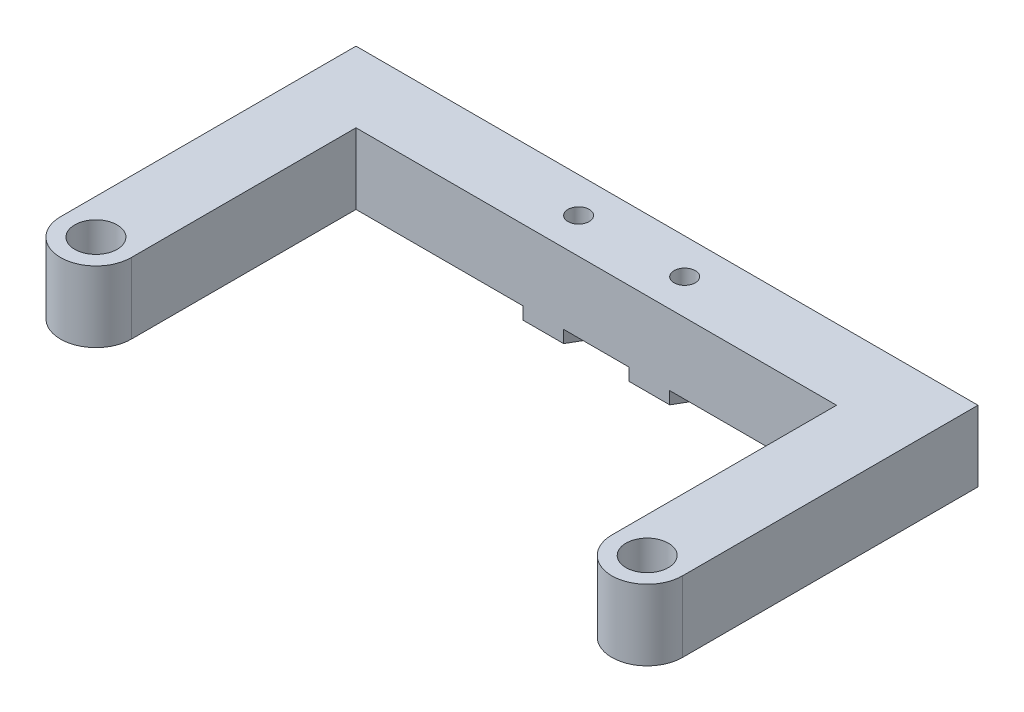
SolidWorks part; units mm, degrees
ref_plane "Front Plane" through (0, 0, 0) normal (0, 0, 1) x (1, 0, 0)
ref_plane "Top Plane" through (0, 0, 0) normal (0, 1, 0) x (1, 0, 0)
ref_plane "Right Plane" through (0, 0, 0) normal (1, 0, 0) x (0, 0, -1)
sketch "Sketch1" plane through (0, 0, 0) normal (0, 1, 0) x (1, 0, 0)
  line L0 (0, 0) -> (0, 45) construction
  line L1 (-38.9711, 22.5) -> (0, 0) construction
  line L3 (-43.9711, 22.5) -> (-33.9711, 22.5)
  line L4 (-43.9711, 22.5) -> (-43.9711, 64.2721)
  line L5 (-43.9711, 64.2721) -> (-33.9711, 64.2721)
  line L6 (-33.9711, 22.5) -> (-33.9711, 64.2721)
  line L7 (-43.9711, 22.5) -> (-33.9711, 64.2721) construction
  line L8 (-43.9711, 64.2721) -> (-33.9711, 22.5) construction
  line L9 (-33.9711, 64.2721) -> (33.9711, 64.2721)
  line L10 (-33.9711, 64.2721) -> (-33.9711, 54.2721)
  line L11 (-33.9711, 54.2721) -> (33.9711, 54.2721)
  line L12 (33.9711, 64.2721) -> (33.9711, 54.2721)
  line L13 (-33.9711, 64.2721) -> (33.9711, 54.2721) construction
  line L14 (-33.9711, 54.2721) -> (33.9711, 64.2721) construction
  line L15 (43.9711, 22.5) -> (33.9711, 22.5)
  line L16 (43.9711, 22.5) -> (43.9711, 64.2721)
  line L17 (43.9711, 64.2721) -> (33.9711, 64.2721)
  line L18 (33.9711, 22.5) -> (33.9711, 64.2721)
  line L19 (43.9711, 22.5) -> (33.9711, 64.2721) construction
  line L20 (43.9711, 64.2721) -> (33.9711, 22.5) construction
  circle A0 centre (0, 0) radius 45 construction
  circle A1 centre (-38.9711, 22.5) radius 1.5
  circle A2 centre (38.9711, 22.5) radius 1.5
  circle A3 centre (-38.9711, 22.5) radius 5
  circle A4 centre (38.9711, 22.5) radius 5
  circle A7 centre (-7.5, 59.2721) radius 1.5
  circle A8 centre (7.5, 59.2721) radius 1.5
  arc A9 (-38.9711, 22.5) -> (38.9711, 22.5) centre (0, 21) cw construction
  point P18 (-38.9711, 43.386)
  point P23 (0, 59.2721)
  point P28 (38.9711, 43.386)
  dimension "D1" = 90
  dimension "D2" = 3
  dimension "D4" = 10
  dimension "D5" = 3
  dimension "D7" = 39
  dimension "D3" = 60
  dimension "D6" = 15
extrude "Boss-Extrude1" add sketch "Sketch1" along normal blind 10
sketch "Sketch2" plane through (0, 0, 0) normal (0, -1, 0) x (1, 0, 0)
  line L0 (-4.6132, -54.2721) -> (-10.3868, -54.2721)
  line L1 (-5.7679, -56.2721) -> (-9.2321, -56.2721)
  line L2 (-9.2321, -56.2721) -> (-10.9641, -59.2721)
  line L3 (-10.9641, -59.2721) -> (-9.2321, -62.2721)
  line L4 (-9.2321, -62.2721) -> (-5.7679, -62.2721)
  line L5 (-5.7679, -62.2721) -> (-4.0359, -59.2721)
  line L6 (-4.0359, -59.2721) -> (-5.7679, -56.2721)
  line L7 (9.2321, -56.2721) -> (5.7679, -56.2721)
  line L8 (5.7679, -56.2721) -> (4.0359, -59.2721)
  line L9 (4.0359, -59.2721) -> (5.7679, -62.2721)
  line L10 (5.7679, -62.2721) -> (9.2321, -62.2721)
  line L11 (9.2321, -62.2721) -> (10.9641, -59.2721)
  line L12 (10.9641, -59.2721) -> (9.2321, -56.2721)
  line L13 (-10.3868, -54.2721) -> (-13.2735, -59.2721)
  line L14 (-13.2735, -59.2721) -> (-10.3868, -64.2721)
  line L15 (-10.3868, -64.2721) -> (-4.6132, -64.2721)
  line L16 (-4.6132, -64.2721) -> (-1.7265, -59.2721)
  line L17 (-1.7265, -59.2721) -> (-4.6132, -54.2721)
  line L19 (10.3868, -54.2721) -> (4.6132, -54.2721)
  line L20 (4.6132, -54.2721) -> (1.7265, -59.2721)
  line L21 (1.7265, -59.2721) -> (4.6132, -64.2721)
  line L22 (4.6132, -64.2721) -> (10.3868, -64.2721)
  line L23 (10.3868, -64.2721) -> (13.2735, -59.2721)
  line L24 (13.2735, -59.2721) -> (10.3868, -54.2721)
  line L26 (-43.9711, -22.5) -> (-43.9711, -64.2721)
  line L28 (-43.9711, -22.5) -> (-43.9711, -64.2721)
  line L34 (-43.9711, -64.2721) -> (43.9711, -64.2721)
  line L35 (-43.9711, -64.2721) -> (43.9711, -64.2721)
  line L36 (43.9711, -64.2721) -> (43.9711, -22.5)
  line L37 (43.9711, -64.2721) -> (43.9711, -22.5)
  line L38 (33.9711, -22.5) -> (33.9711, -54.2721)
  line L39 (33.9711, -22.5) -> (33.9711, -54.2721)
  line L40 (33.9711, -54.2721) -> (-33.9711, -54.2721)
  line L41 (33.9711, -54.2721) -> (-33.9711, -54.2721)
  line L42 (-33.9711, -54.2721) -> (-33.9711, -22.5)
  line L43 (-33.9711, -54.2721) -> (-33.9711, -22.5)
  circle A0 centre (-7.5, -59.2721) radius 1.5 construction
  circle A1 centre (7.5, -59.2721) radius 1.5 construction
  circle A2 centre (-7.5, -59.2721) radius 1.5
  circle A3 centre (7.5, -59.2721) radius 1.5
  circle A4 centre (-7.5, -59.2721) radius 3 construction
  circle A5 centre (7.5, -59.2721) radius 3 construction
  circle A6 centre (7.5, -59.2721) radius 5 construction
  arc A9 (43.9711, -22.5) -> (33.9711, -22.5) centre (38.9711, -22.5) ccw
  arc A10 (-33.9711, -22.5) -> (-43.9711, -22.5) centre (-38.9711, -22.5) ccw
  arc A12 (43.9711, -22.5) -> (33.9711, -22.5) centre (38.9711, -22.5) ccw
  arc A14 (-33.9711, -22.5) -> (-43.9711, -22.5) centre (-38.9711, -22.5) ccw
  dimension "D1" = 6
  dimension "D2" = 2
  dimension "D3" = 0
extrude "Boss-Extrude2" add sketch "Sketch2" along normal blind 1.75
sketch "Sketch3" plane through (0, 10, 0) normal (0, 1, 0) x (1, 0, 0)
  line L18 (-33.9711, 22.5) -> (-33.9711, 54.2721)
  line L19 (-33.9711, 54.2721) -> (33.9711, 54.2721)
  line L20 (33.9711, 54.2721) -> (33.9711, 22.5)
  line L21 (43.9711, 22.5) -> (43.9711, 64.2721)
  line L22 (43.9711, 64.2721) -> (-43.9711, 64.2721)
  line L23 (-43.9711, 64.2721) -> (-43.9711, 22.5)
  line L24 (-33.9711, 22.5) -> (-33.9711, 54.2721)
  line L25 (-33.9711, 54.2721) -> (33.9711, 54.2721)
  line L26 (33.9711, 54.2721) -> (33.9711, 22.5)
  line L27 (43.9711, 22.5) -> (43.9711, 64.2721)
  line L28 (43.9711, 64.2721) -> (-43.9711, 64.2721)
  line L29 (-43.9711, 64.2721) -> (-43.9711, 22.5)
  circle A0 centre (-38.9711, 22.5) radius 3
  circle A1 centre (38.9711, 22.5) radius 3
  arc A3 (-43.9711, 22.5) -> (-33.9711, 22.5) centre (-38.9711, 22.5) ccw
  arc A4 (33.9711, 22.5) -> (43.9711, 22.5) centre (38.9711, 22.5) ccw
  dimension "D1" = 6
  dimension "D3" = 0
extrude "Cut-Extrude1" cut sketch "Sketch3" against normal blind 5
